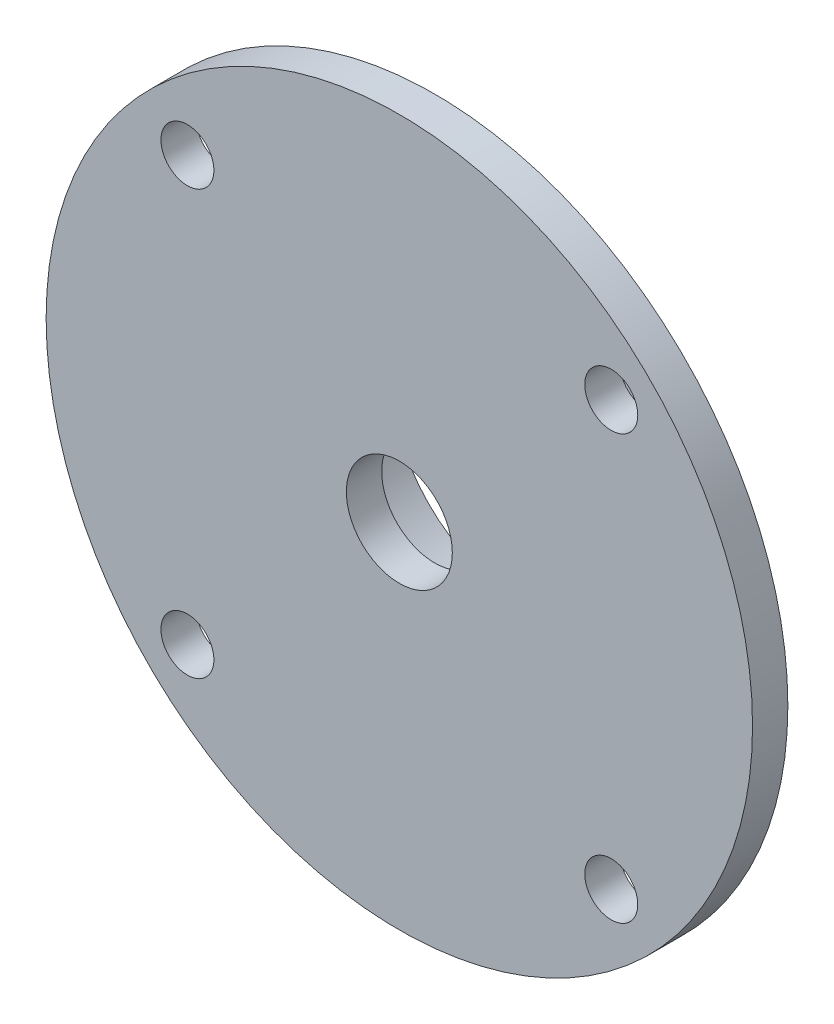
SolidWorks part; units mm, degrees
ref_plane "前视基准面" through (0, 0, 0) normal (0, 0, 1) x (1, 0, 0)
ref_plane "上视基准面" through (0, 0, 0) normal (0, 1, 0) x (1, 0, 0)
ref_plane "右视基准面" through (0, 0, 0) normal (1, 0, 0) x (0, 0, -1)
other "Configuration Table"
sketch "草图1" plane through (0, 0, 0) normal (0, 0, 1) x (1, 0, 0)
  line L5 (-15, 15) -> (15, -15) construction
  line L6 (-15, -15) -> (15, 15) construction
  circle A0 centre (-12, 12) radius 1.5
  circle A1 centre (12, 12) radius 1.5
  circle A2 centre (12, -12) radius 1.5
  circle A3 centre (-12, -12) radius 1.5
  circle A4 centre (0, 0) radius 3
  circle A5 centre (0, 0) radius 20
  point P0 (0, 0)
  point P17 (0, 0)
  dimension "D4" = 4
extrude "凸台-拉伸1" add sketch "草图1" along normal blind 2
sketch "草图3" plane through (0, 0, 0) normal (0, 0, -1) x (-1, 0, 0)
  circle A0 centre (0, 0) radius 11
  circle A1 centre (0, 0) radius 7.5
  dimension "D1" = 22
  dimension "D2" = 15
extrude "凸台-拉伸2" add sketch "草图3" along normal blind 5
